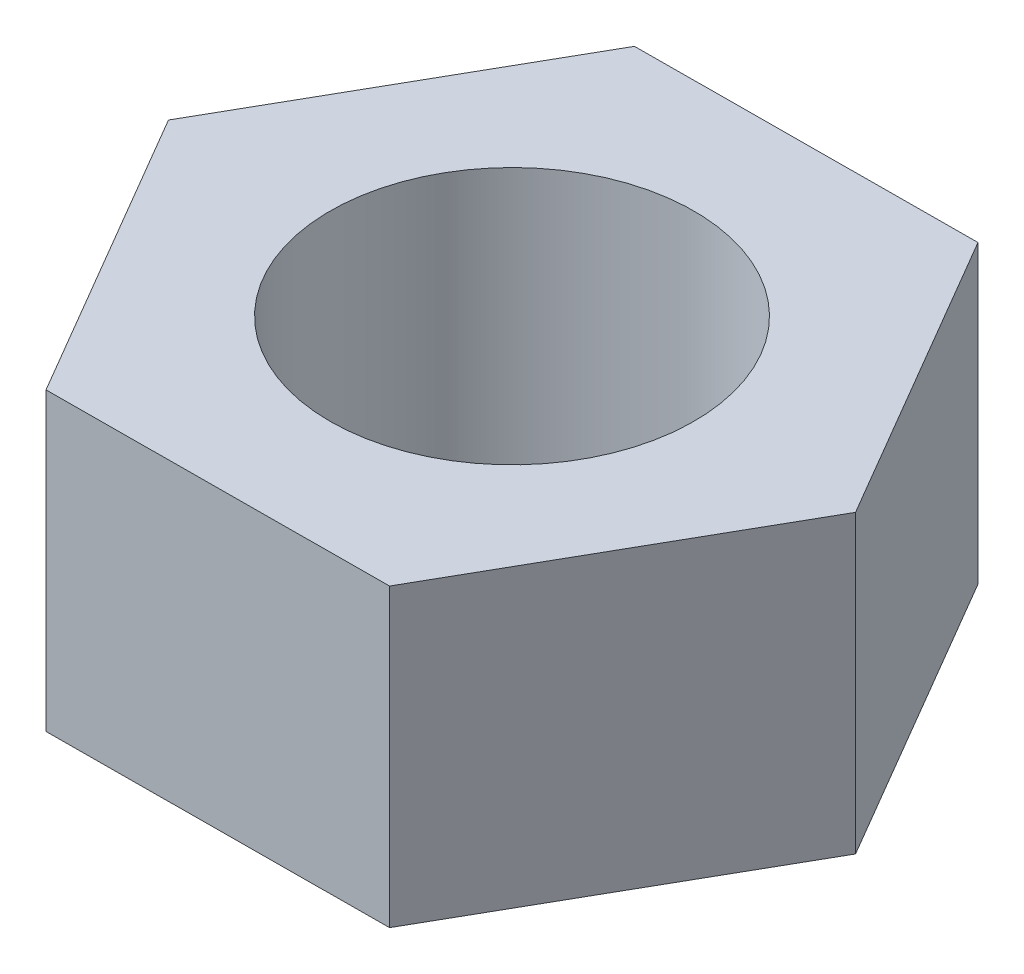
SolidWorks part; units mm, degrees
ref_plane "Front Plane" through (0, 0, 0) normal (0, 0, 1) x (1, 0, 0)
ref_plane "Top Plane" through (0, 0, 0) normal (0, 1, 0) x (1, 0, 0)
ref_plane "Right Plane" through (0, 0, 0) normal (1, 0, 0) x (0, 0, -1)
sketch "Sketch1" plane through (0, 0, 0) normal (0, 1, 0) x (1, 0, 0)
  line L1 (3.7889, -6.479) -> (7.5054, 0.0418)
  line L2 (7.5054, 0.0418) -> (3.7165, 6.5208)
  line L3 (3.7165, 6.5208) -> (-3.7889, 6.479)
  line L4 (-3.7889, 6.479) -> (-7.5054, -0.0418)
  line L5 (-7.5054, -0.0418) -> (-3.7165, -6.5208)
  line L6 (-3.7165, -6.5208) -> (3.7889, -6.479)
  circle A0 centre (0, 0) radius 6.5 construction
  dimension "D1" = 13
extrude "Boss-Extrude1" add sketch "Sketch1" along normal blind 6.5
sketch "Sketch2" plane through (0, 6.5, 0) normal (0, 1, 0) x (1, 0, 0)
  circle A0 centre (0, 0) radius 4
  dimension "D1" = 8
extrude "Cut-Extrude1" cut sketch "Sketch2" against normal through all
